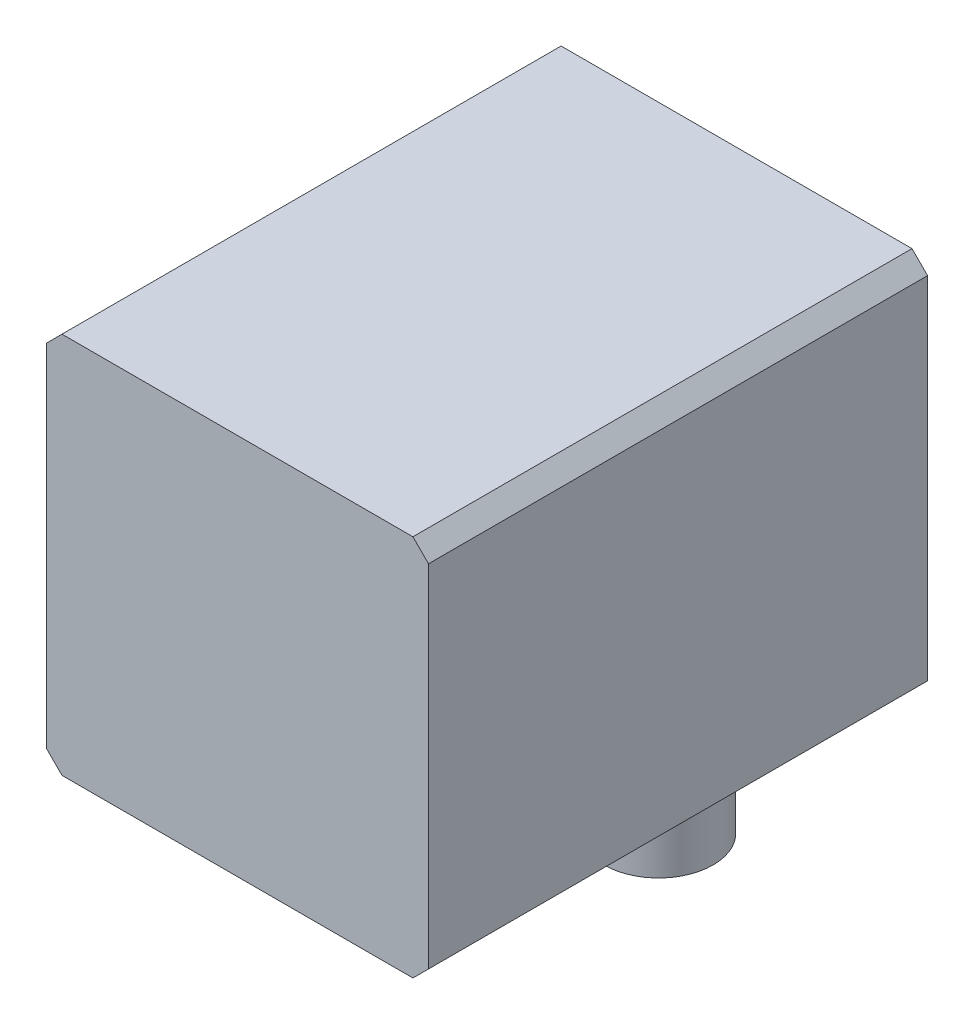
SolidWorks part; units mm, degrees
ref_plane "前视基准面" through (0, 0, 0) normal (0, 0, 1) x (1, 0, 0)
ref_plane "上视基准面" through (0, 0, 0) normal (0, 1, 0) x (1, 0, 0)
ref_plane "右视基准面" through (0, 0, 0) normal (1, 0, 0) x (0, 0, -1)
sketch "草图6" plane through (0, 0, 0) normal (0, 0, 1) x (1, 0, 0)
  line L1 (-61.25, 61.25) -> (61.25, 61.25)
  line L2 (-61.25, 61.25) -> (-61.25, -61.25)
  line L3 (-61.25, -61.25) -> (61.25, -61.25)
  line L4 (61.25, 61.25) -> (61.25, -61.25)
  dimension "D1" = 122.5
  dimension "D2" = 61.25
  dimension "D3" = 61.25
extrude "凸台-拉伸5" add sketch "草图6" along normal blind 160
sketch "草图7" plane through (0, -61.25, 0) normal (0, -1, 0) x (1, 0, 0)
  circle A0 centre (0, 25) radius 17.5
  dimension "D1" = 35
  dimension "D2" = 25
extrude "凸台-拉伸6" add sketch "草图7" along normal blind 55.5
sketch "草图8" plane through (0, -116.75, 0) normal (0, -1, 0) x (1, 0, 0)
  circle A0 centre (0, 25) radius 6
  dimension "D1" = 12
extrude "凸台-拉伸7" add sketch "草图8" along normal blind 5
chamfer "倒角1" distance 5 angle 45 4 edges at (61.25, 61.25, 80) (61.25, -61.25, 80) (-61.25, 61.25, 80) (-61.25, -61.25, 80)
sketch "草图9" plane through (0, 0, 0) normal (0, 0, -1) x (-1, 0, 0)
  line L1 (-48, 48) -> (48, 48) construction
  line L2 (-48, 48) -> (-48, -48) construction
  line L3 (-48, -48) -> (48, -48) construction
  line L4 (48, 48) -> (48, -48) construction
  circle A0 centre (-48, 48) radius 2.75
  circle A1 centre (48, 48) radius 2.75
  circle A2 centre (48, -48) radius 2.75
  circle A3 centre (-48, -48) radius 2.75
  dimension "D4" = 5.5
  dimension "D1" = 96
  dimension "D2" = 48
  dimension "D3" = 48
extrude "切除-拉伸1" cut sketch "草图9" against normal blind 20
